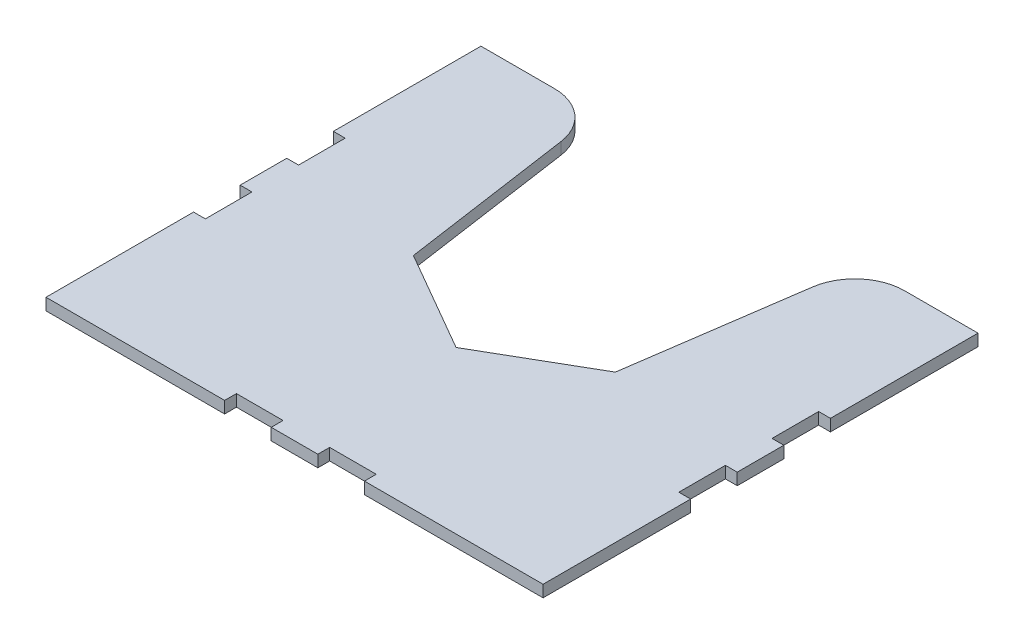
SolidWorks part; units mm, degrees
ref_plane "Front Plane" through (0, 0, 0) normal (0, 0, 1) x (1, 0, 0)
ref_plane "Top Plane" through (0, 0, 0) normal (0, 1, 0) x (1, 0, 0)
ref_plane "Right Plane" through (0, 0, 0) normal (1, 0, 0) x (0, 0, -1)
sketch "Sketch1" plane through (0, 0, 0) normal (0, 1, 0) x (1, 0, 0)
  line L1 (0, 0) -> (203.2, 0)
  line L2 (0, 0) -> (0, 177.8)
  line L3 (0, 177.8) -> (203.2, 177.8)
  line L4 (203.2, 0) -> (203.2, 177.8)
  dimension "D1" = 203.2
  dimension "D2" = 177.8
extrude "Base" add sketch "Sketch1" along normal blind 4.826
sketch "Sketch2" plane through (0, 4.826, 0) normal (0, 1, 0) x (1, 0, 0)
  line L0 (203.2, 177.8) -> (0, 177.8) construction
  line L1 (47.625, 177.8) -> (0, 177.8) construction
  line L2 (155.575, 177.8) -> (203.2, 177.8) construction
  line L3 (60.325, 89.8701) -> (101.6, 66.04)
  line L4 (0, 0) -> (203.2, 0) construction
  line L5 (60.325, 89.8701) -> (0, 89.8701) construction
  line L6 (0, 177.8) -> (0, 0) construction
  line L7 (142.875, 89.8701) -> (203.2, 89.8701) construction
  line L8 (203.2, 0) -> (203.2, 177.8) construction
  line L9 (60.325, 89.8701) -> (47.625, 177.8)
  line L10 (47.625, 177.8) -> (155.575, 177.8)
  line L11 (155.575, 177.8) -> (142.875, 89.8701)
  line L12 (101.6, 66.04) -> (142.875, 89.8701)
  line L13 (101.6, 66.04) -> (0, 66.04) construction
  line L14 (101.6, 66.04) -> (203.2, 66.04) construction
  dimension "D1" = 82.55
  dimension "D2" = 107.95
  dimension "D3" = 66.04
  dimension "D4" = 120
extrude "Center Cut" cut sketch "Sketch2" against normal through all
fillet "Leading Edge Fillet" radius 20.32 2 edges at (155.575, 2.413, -177.8) (47.625, 2.413, -177.8)
sketch "Sketch3" plane through (0, 4.826, 0) normal (0, 1, 0) x (1, 0, 0)
  line L0 (0, 177.8) -> (0, 0) construction
  line L1 (0, 117.475) -> (4.826, 117.475)
  line L2 (0, 117.475) -> (0, 98.425)
  line L3 (0, 98.425) -> (4.826, 98.425)
  line L4 (4.826, 117.475) -> (4.826, 98.425)
  line L5 (4.826, 117.475) -> (4.826, 177.8) construction
  line L6 (0, 79.375) -> (4.826, 79.375)
  line L7 (0, 79.375) -> (0, 60.325)
  line L8 (0, 60.325) -> (4.826, 60.325)
  line L9 (4.826, 79.375) -> (4.826, 60.325)
  line L10 (30.029, 177.8) -> (0, 177.8) construction
  line L11 (4.826, 98.425) -> (4.826, 79.375) construction
  line L12 (4.826, 60.325) -> (4.826, 0) construction
  line L13 (0, 0) -> (203.2, 0) construction
  line L14 (101.6, 0) -> (101.6, 50000) construction
  line L15 (198.374, 60.325) -> (198.374, 0) construction
  line L16 (198.374, 98.425) -> (198.374, 79.375) construction
  line L17 (198.374, 117.475) -> (198.374, 177.8) construction
  line L18 (198.374, 79.375) -> (198.374, 60.325)
  line L19 (203.2, 60.325) -> (198.374, 60.325)
  line L20 (203.2, 79.375) -> (203.2, 60.325)
  line L21 (203.2, 79.375) -> (198.374, 79.375)
  line L22 (198.374, 117.475) -> (198.374, 98.425)
  line L23 (203.2, 98.425) -> (198.374, 98.425)
  line L24 (203.2, 117.475) -> (203.2, 98.425)
  line L25 (203.2, 117.475) -> (198.374, 117.475)
  point P18 (101.6, 0)
  dimension "D1" = 19.05
  dimension "D2" = 4.826
extrude "Side Slots" cut sketch "Sketch3" against normal through all
sketch "Sketch4" plane through (0, 4.826, 0) normal (0, 1, 0) x (1, 0, 0)
  line L0 (0, 0) -> (203.2, 0) construction
  line L1 (73.025, 0) -> (92.075, 0)
  line L2 (73.025, 0) -> (73.025, 4.826)
  line L3 (73.025, 4.826) -> (92.075, 4.826)
  line L4 (92.075, 0) -> (92.075, 4.826)
  line L5 (73.025, 4.826) -> (0, 4.826) construction
  line L6 (111.125, 0) -> (130.175, 0)
  line L7 (111.125, 0) -> (111.125, 4.826)
  line L8 (111.125, 4.826) -> (130.175, 4.826)
  line L9 (130.175, 0) -> (130.175, 4.826)
  line L10 (0, 60.325) -> (0, 0) construction
  line L11 (92.075, 4.826) -> (111.125, 4.826) construction
  line L12 (130.175, 4.826) -> (203.2, 4.826) construction
  line L13 (203.2, 0) -> (203.2, 60.325) construction
  dimension "D1" = 19.05
  dimension "D2" = 4.826
extrude "Rear Slots" cut sketch "Sketch4" against normal through all
equation "\"material\"= \"gmaterial@Forklift_v2.assembly\""
equation "\"D1@Base\"=\"material\""
equation "\"tab\"= \"gtab@Forklift_v2.assembly\""
equation "\"D1@Sketch3\"=\"tab\""
equation "\"D2@Sketch3\"=\"material\""
equation "\"D1@Sketch4\"=\"tab\""
equation "\"D2@Sketch4\"=\"material\""
